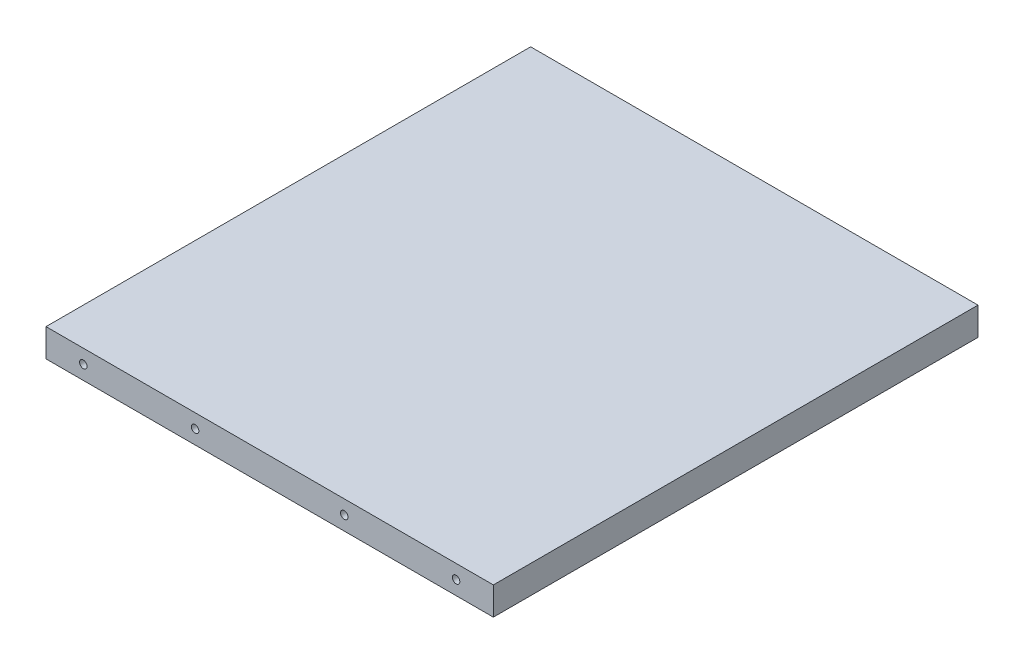
SolidWorks part; units mm, degrees
ref_plane "Front Plane" through (0, 0, 0) normal (0, 0, 1) x (1, 0, 0)
ref_plane "Top Plane" through (0, 0, 0) normal (0, 1, 0) x (1, 0, 0)
ref_plane "Right Plane" through (0, 0, 0) normal (1, 0, 0) x (0, 0, -1)
sketch "Sketch2" plane through (0, 0, 0) normal (0, 1, 0) x (1, 0, 0)
  line L1 (-152.4, -165.1) -> (152.4, -165.1)
  line L2 (-152.4, -165.1) -> (-152.4, 165.1)
  line L3 (-152.4, 165.1) -> (152.4, 165.1)
  line L4 (152.4, -165.1) -> (152.4, 165.1)
  line L5 (-152.4, -165.1) -> (152.4, 165.1) construction
  line L6 (-152.4, 165.1) -> (152.4, -165.1) construction
  point P0 (0, 0)
  dimension "D1" = 304.8
  dimension "D2" = 330.2
extrude "Boss-Extrude1" add sketch "Sketch2" along normal mid plane 19.05
sketch "Sketch3" plane through (0, 0, 165.1) normal (0, 0, 1) x (1, 0, 0)
  point P0 (-127, 0)
  point P1 (-50.8, 0)
  point P3 (50.8, 0)
  point P5 (127, 0)
hole_wizard "1/4-20 Tapped Hole1" positions "Sketch4" profile "Sketch6" tap size "1/4-20" standard "ANSI Inch"
sketch "Sketch4" plane through (0, 0, 165.1) normal (0, 0, 1) x (1, 0, 0)
  point P0 (127, 0)
  point P3 (50.8, 0)
  point P6 (-50.8, 0)
  point P9 (-127, 0)
cosmetic thread "Hole Thread1" parameters "D2"=6.35
cosmetic thread "Hole Thread2" parameters "D2"=6.35
cosmetic thread "Hole Thread3" parameters "D2"=6.35
cosmetic thread "Hole Thread4" parameters "D2"=6.35
sketch "Sketch6" plane through (127, 0, 165.1) normal (1, 0, 0) x (0, -1, 0)
  line L0 (0, 0) -> (0, 39.6338)
  line L1 (0, 39.6338) -> (2.5527, 38.1)
  line L2 (2.5527, 38.1) -> (2.5527, 0)
  line L5 (2.5527, 0) -> (0, 0)
  line L10 (0, 39.6338) -> (-2.5527, 38.1) construction
  line L11 (0, -6.35) -> (0, 107.95) construction
  dimension "Tap Drill Dia." = 5.1054
  dimension "Tap Drill Depth" = 38.1
  dimension "Drill Angle" = 118
